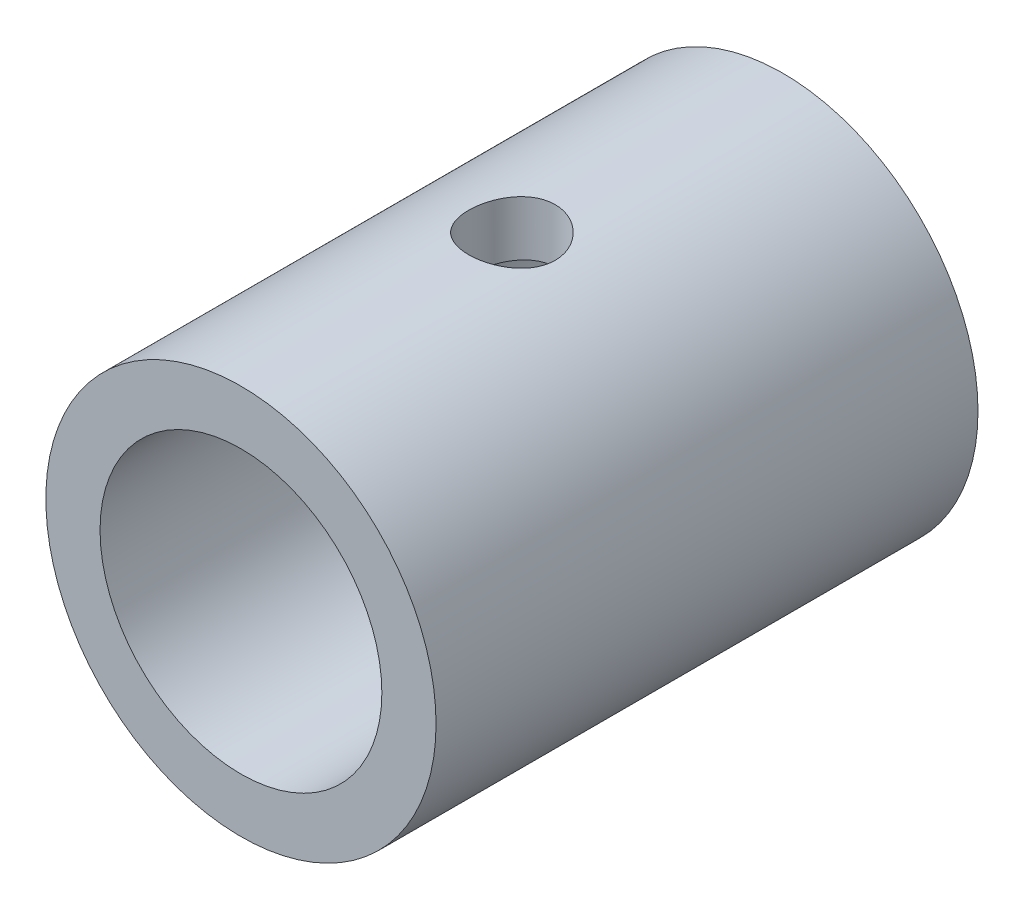
SolidWorks part; units mm, degrees
material "Aluminum Bronze"
ref_plane "Front Plane" through (0, 0, 0) normal (0, 0, 1) x (1, 0, 0)
ref_plane "Top Plane" through (0, 0, 0) normal (0, 1, 0) x (1, 0, 0)
ref_plane "Right Plane" through (0, 0, 0) normal (1, 0, 0) x (0, 0, -1)
sketch "Sketch1" plane through (0, 0, 0) normal (0, 0, 1) x (1, 0, 0)
  circle A0 centre (0, 0) radius 9
  circle A1 centre (0, 0) radius 6.5
  dimension "D1" = 18
  dimension "D2" = 13
extrude "Boss-Extrude1" add sketch "Sketch1" along normal mid plane 25 contours A0 A1
sketch "Sketch2" plane through (0, 0, 0) normal (0, 1, 0) x (1, 0, 0)
  circle A0 centre (0, 0) radius 2
  dimension "D1" = 4
extrude "Cut-Extrude1" cut sketch "Sketch2" along normal through all
cosmetic thread "Cosmetic Thread1" parameters "D2"=5
